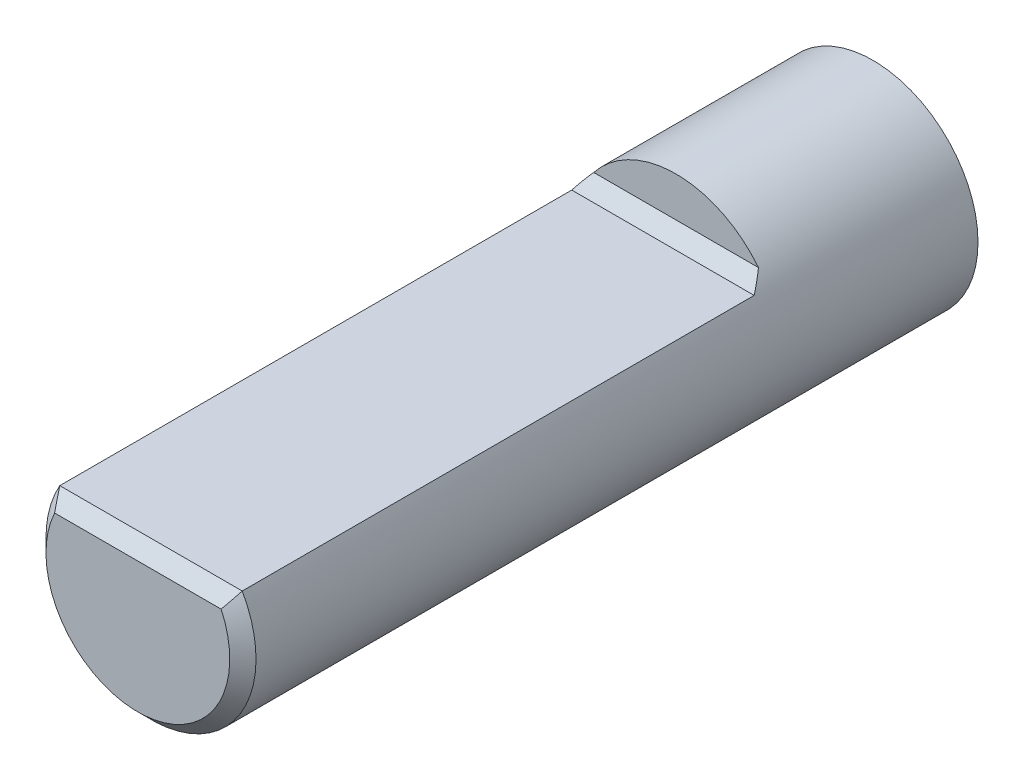
SolidWorks part; units mm, degrees
ref_plane "Front Plane" through (0, 0, 0) normal (0, 0, 1) x (1, 0, 0)
ref_plane "Top Plane" through (0, 0, 0) normal (0, 1, 0) x (1, 0, 0)
ref_plane "Right Plane" through (0, 0, 0) normal (1, 0, 0) x (0, 0, -1)
sketch "Sketch2" plane through (0, 0, 0) normal (0, 0, 1) x (1, 0, 0)
  circle A0 centre (0, 0) radius 4
  dimension "D1" = 8
extrude "Boss-Extrude1" add sketch "Sketch2" along normal blind 28
sketch "Sketch4" plane through (0, 0, 28) normal (0, 0, 1) x (1, 0, 0)
  line L0 (-3.475, 1.981) -> (3.475, 1.981)
  line L1 (0, 4) -> (-3.475, 4)
  line L2 (-3.475, 4) -> (-3.475, 1.981)
  line L3 (0, 4) -> (3.475, 4)
  line L4 (3.475, 4) -> (3.475, 1.981)
  circle A1 centre (0, 0) radius 4 construction
  dimension "D1" = 6.95
extrude "Cut-Extrude1" cut sketch "Sketch4" against normal blind 20.5
chamfer "Chamfer2" distance 0.5 angle 45 3 edges at (0, -4, 28) (0, 1.981, 28) (0, 1.981, 7.5)
